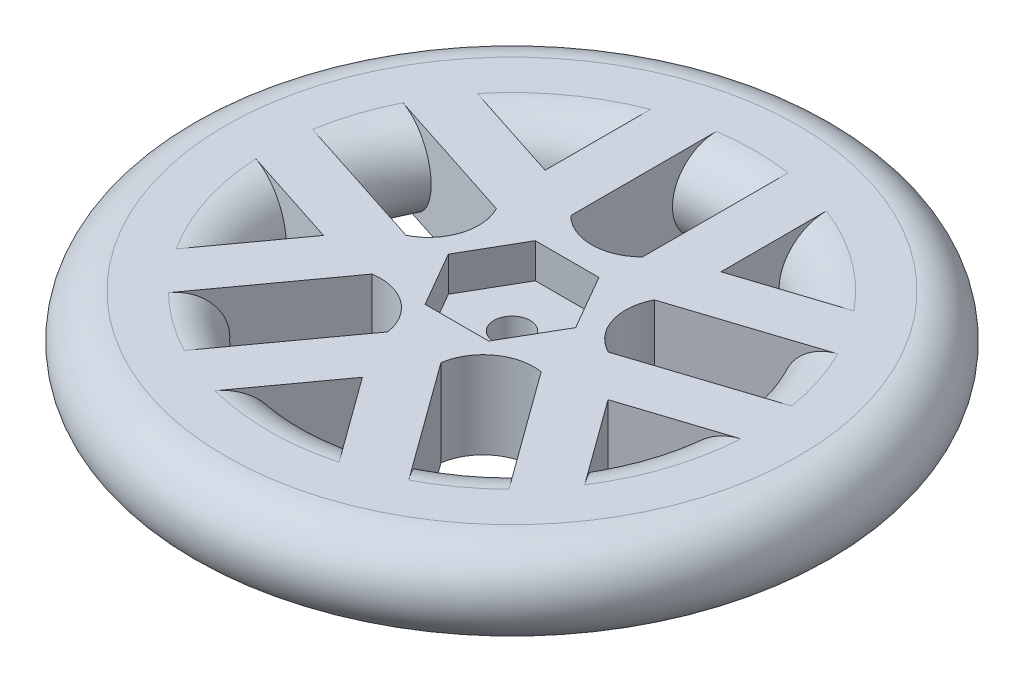
SolidWorks part; units mm, degrees
ref_plane "前视基准面" through (0, 0, 0) normal (0, 0, 1) x (1, 0, 0)
ref_plane "上视基准面" through (0, 0, 0) normal (0, 1, 0) x (1, 0, 0)
ref_plane "右视基准面" through (0, 0, 0) normal (1, 0, 0) x (0, 0, -1)
other "Configuration Table"
sketch "草图1" plane through (0, 0, 0) normal (1, 0, 0) x (0, 0, -1)
  line L0 (0, 0) -> (0, 6.1282) construction
  line L1 (0, 0) -> (9, 0)
  line L2 (0, 0) -> (0, -10)
  line L3 (0, -10) -> (9, -10)
  line L4 (9, 0) -> (9, -10)
  dimension "D1" = 9
  dimension "D2" = 10
revolve "旋转1" add sketch "草图1" angle 360 about L0
sketch "草图2" plane through (0, 0, 0) normal (0, 1, 0) x (1, 0, 0)
  line L1 (7.2733, -0.1394) -> (3.7574, 6.2291)
  line L2 (3.7574, 6.2291) -> (-3.5159, 6.3685)
  line L3 (-3.5159, 6.3685) -> (-7.2733, 0.1394)
  line L4 (-7.2733, 0.1394) -> (-3.7574, -6.2291)
  line L5 (-3.7574, -6.2291) -> (3.5159, -6.3685)
  line L6 (3.5159, -6.3685) -> (7.2733, -0.1394)
  circle A0 centre (0, 0) radius 6.3 construction
  dimension "D1" = 12.6
extrude "切除-拉伸1" cut sketch "草图2" against normal blind 4
sketch "草图4" plane through (0, 0, 0) normal (0, 0, 1) x (1, 0, 0)
  line L0 (0, 0) -> (0, 13.7912) construction
  line L1 (28, 0) -> (33, 0)
  line L4 (33, -10) -> (28, -10)
  arc A0 (28, 0) -> (28, -10) centre (28, -5) ccw
  arc A2 (33, -10) -> (33, 0) centre (33, -5) ccw
  point P4 (0, 0)
  point P6 (0, 0)
  dimension "D1" = 10
  dimension "D4" = 10
  dimension "D2" = 28
  dimension "D3" = 5
  dimension "D5" = 5
revolve "旋转2" add sketch "草图4" angle 360 about L0
sketch "草图5" plane through (0, 0, 0) normal (0, 1, 0) x (1, 0, 0)
  line L0 (0, 30) -> (0, 0) construction
  line L1 (0, 30) -> (-28.5317, 9.2705) construction
  line L2 (-28.5317, 9.2705) -> (-17.6336, -24.2705) construction
  line L3 (-17.6336, -24.2705) -> (17.6336, -24.2705) construction
  line L4 (17.6336, -24.2705) -> (28.5317, 9.2705) construction
  line L5 (28.5317, 9.2705) -> (0, 30) construction
  line L6 (0, 0) -> (-28.5317, 9.2705) construction
  line L7 (-17.6336, -24.2705) -> (0, 0) construction
  line L8 (0, 0) -> (17.6336, -24.2705) construction
  line L9 (28.5317, 9.2705) -> (0, 0) construction
  line L10 (0, 0) -> (-14.2658, 19.6353) construction
  line L11 (0, 0) -> (14.2658, 19.6353) construction
  line L12 (0, 0) -> (23.0826, -7.5) construction
  line L13 (0, 0) -> (23.0826, -7.5) construction
  line L14 (0, 0) -> (0, -24.2705) construction
  line L15 (0, 0) -> (-23.0826, -7.5) construction
  line L16 (-7.1329, 9.8176) -> (-7.1329, 27.0762) construction
  line L17 (7.1329, 9.8176) -> (7.1329, 27.0762) construction
  line L18 (4.1329, 10.9069) -> (4.1329, 27.0762)
  line L19 (-4.1329, 10.9069) -> (-4.1329, 27.0762)
  line L20 (10.1329, 8.9205) -> (10.1329, 27.0762)
  line L21 (-10.1329, 8.9205) -> (-10.1329, 27.0762)
  line L22 (4.1329, 27.0762) -> (4.1329, 29.0762)
  line L23 (4.1329, 29.0762) -> (10.1329, 29.0762)
  line L24 (10.1329, 29.0762) -> (10.1329, 27.0762)
  line L25 (-10.1329, 27.0762) -> (-10.1329, 29.0762)
  line L26 (-10.1329, 29.0762) -> (-4.1329, 29.0762)
  line L27 (-4.1329, 29.0762) -> (-4.1329, 27.0762)
  line L28 (11.6152, -6.8804) -> (28.8823, -1.27)
  line L29 (11.6502, -0.5602) -> (27.0282, 4.4364)
  line L30 (27.0282, 4.4364) -> (28.9303, 5.0544)
  line L31 (28.9303, 5.0544) -> (30.7844, -0.6519)
  line L32 (30.7844, -0.6519) -> (28.8823, -1.27)
  line L33 (26.376, 12.9157) -> (24.4739, 12.2977)
  line L34 (24.5219, 18.622) -> (26.376, 12.9157)
  line L35 (22.6198, 18.004) -> (24.5219, 18.622)
  line L36 (9.0959, 7.301) -> (24.4739, 12.2977)
  line L37 (5.3527, 12.3936) -> (22.6198, 18.004)
  line L38 (-2.9544, -13.1728) -> (7.7173, -27.8611)
  line L39 (3.0673, -11.2531) -> (12.5714, -24.3344)
  line L40 (12.5714, -24.3344) -> (13.747, -25.9524)
  line L41 (13.747, -25.9524) -> (8.8929, -29.4791)
  line L42 (8.8929, -29.4791) -> (7.7173, -27.8611)
  line L43 (20.4342, -21.0939) -> (19.2586, -19.4758)
  line L44 (25.2883, -17.5672) -> (20.4342, -21.0939)
  line L45 (24.1127, -15.9491) -> (25.2883, -17.5672)
  line L46 (9.7545, -6.3946) -> (19.2586, -19.4758)
  line L47 (13.4411, -1.2609) -> (24.1127, -15.9491)
  line L48 (-13.4411, -1.2609) -> (-24.1127, -15.9491)
  line L49 (-9.7545, -6.3946) -> (-19.2586, -19.4758)
  line L50 (-19.2586, -19.4758) -> (-20.4342, -21.0939)
  line L51 (-20.4342, -21.0939) -> (-25.2883, -17.5672)
  line L52 (-25.2883, -17.5672) -> (-24.1127, -15.9491)
  line L53 (-13.747, -25.9524) -> (-12.5714, -24.3344)
  line L54 (-8.8929, -29.4791) -> (-13.747, -25.9524)
  line L55 (-7.7173, -27.8611) -> (-8.8929, -29.4791)
  line L56 (-3.0673, -11.2531) -> (-12.5714, -24.3344)
  line L57 (2.9544, -13.1728) -> (-7.7173, -27.8611)
  line L58 (-5.3527, 12.3936) -> (-22.6198, 18.004)
  line L59 (-9.0959, 7.301) -> (-24.4739, 12.2977)
  line L60 (-24.4739, 12.2977) -> (-26.376, 12.9157)
  line L61 (-26.376, 12.9157) -> (-24.5219, 18.622)
  line L62 (-24.5219, 18.622) -> (-22.6198, 18.004)
  line L63 (-28.9303, 5.0544) -> (-27.0282, 4.4364)
  line L64 (-30.7844, -0.6519) -> (-28.9303, 5.0544)
  line L65 (-28.8823, -1.27) -> (-30.7844, -0.6519)
  line L66 (-11.6502, -0.5602) -> (-27.0282, 4.4364)
  line L67 (-11.6152, -6.8804) -> (-28.8823, -1.27)
  circle A0 centre (0, 0) radius 24.2705 construction
  arc A1 (-7.1329, 9.8176) -> (7.1329, 9.8176) centre (0, 15) ccw construction
  circle A2 centre (0, 0) radius 28 construction
  arc A3 (-4.1329, 10.9069) -> (4.1329, 10.9069) centre (0, 15) ccw
  arc A4 (-10.1329, 8.9205) -> (10.1329, 8.9205) centre (0, 15) ccw
  arc A5 (9.0959, 7.301) -> (11.6502, -0.5602) centre (14.2658, 4.6353) ccw
  arc A6 (5.3527, 12.3936) -> (11.6152, -6.8804) centre (14.2658, 4.6353) ccw
  arc A7 (9.7545, -6.3946) -> (3.0673, -11.2531) centre (8.8168, -12.1353) ccw
  arc A8 (13.4411, -1.2609) -> (-2.9544, -13.1728) centre (8.8168, -12.1353) ccw
  arc A9 (-3.0673, -11.2531) -> (-9.7545, -6.3946) centre (-8.8168, -12.1353) ccw
  arc A10 (2.9544, -13.1728) -> (-13.4411, -1.2609) centre (-8.8168, -12.1353) ccw
  arc A11 (-11.6502, -0.5602) -> (-9.0959, 7.301) centre (-14.2658, 4.6353) ccw
  arc A12 (-11.6152, -6.8804) -> (-5.3527, 12.3936) centre (-14.2658, 4.6353) ccw
  point P16 (0, 0)
  point P94 (0, 0)
  circle M15 centre (0, 0) radius 28
  dimension "D2" = 17.6336
  dimension "D5" = 2
  dimension "D6" = 2
  dimension "D7" = 5
  dimension "D3" = 3
  dimension "D4" = 3
  dimension "D1" = 5
extrude "凸台-拉伸1" add sketch "草图5" against normal blind 10 contours A12 A4 A6 L37 L20 L22 L18 A3 L19 L27 L21 L58 M15 | L37 A6 A4 L20 | A8 L47 L28 L30 L29 A5 L36 L33 L37 L20 A4 A6 M15 | L47 A8 A6 L28 | L32 L31 L30 L28 M15 | L37 L33 L34 L35 M15 | L24 L23 L22 L20 M15 | L27 L26 L25 L21 M15 | A4 A12 L58 L21 | A10 A12 A4 L21 L58 L60 L59 A11 L66 L63 L67 L48 M15 | L62 L61 L60 L58 M15 | L67 L63 L64 L65 M15 | L67 A12 A10 L48 | A12 L67 L48 L50 L49 A9 L56 L53 L57 L38 A8 A10 M15 | L52 L51 L50 L48 M15 | L57 L53 L54 L55 M15 | L57 A10 A8 L38 | A10 L57 L38 L40 L39 A7 L46 L43 L47 L28 A6 A8 M15 | L42 L41 L40 L38 M15 | L47 L43 L44 L45 M15 | A12 A10 A8 A6 A4
sketch "草图6" plane through (0, -10, 0) normal (0, -1, 0) x (1, 0, 0)
  line L2 (-22.6517, 17.0006) -> (-12.291, 2.7403)
  line L3 (1.192, 12.5362) -> (-9.1687, 26.7965)
  line L4 (-22.0484, 18.2117) -> (-11.5413, 3.75)
  line L5 (0, 12.1353) -> (-10.5071, 26.597)
  line L6 (-21.8811, 17.9815) -> (-11.5413, 3.75) construction
  line L7 (0, 12.1353) -> (-10.5071, 26.597) construction
  line L8 (-21.0776, 18.9171) -> (-10.809, 4.7836)
  line L9 (-1.2093, 11.7582) -> (-11.4779, 25.8916)
  line L10 (12.291, 2.7403) -> (22.6517, 17.0006)
  line L11 (-22.0484, 18.2117) -> (-11.5413, 3.75) construction
  line L12 (-23.0192, 17.5064) -> (-12.291, 2.7403) construction
  line L13 (1.192, 12.5362) -> (-9.5362, 27.3023) construction
  line L14 (10.809, 4.7836) -> (21.0776, 18.9171)
  line L15 (11.4779, 25.8916) -> (1.2093, 11.7582)
  line L16 (9.1687, 26.7965) -> (-1.192, 12.5362)
  line L17 (6.4043, -10.8426) -> (23.1683, -16.2896)
  line L18 (7.8897, -8.8018) -> (24.5045, -14.2002)
  line L19 (28.1713, -2.9152) -> (11.5564, 2.4833)
  line L20 (28.3183, -0.4394) -> (11.5543, 5.0075)
  line L21 (-8.3329, -9.4414) -> (-8.3329, -27.0681)
  line L22 (-5.9329, -10.2234) -> (-5.9329, -27.6933)
  line L23 (5.9329, -27.6933) -> (5.9329, -10.2234)
  line L24 (8.3329, -27.0681) -> (8.3329, -9.4414)
  line L25 (-11.5543, 5.0075) -> (-28.3183, -0.4394)
  line L26 (-11.5564, 2.4833) -> (-28.1713, -2.9152)
  line L27 (-24.5045, -14.2002) -> (-7.8897, -8.8018)
  line L28 (-23.1683, -16.2896) -> (-6.4043, -10.8426)
  arc A1 (-12.291, 2.7403) -> (1.192, 12.5362) centre (-8.8168, 12.1353) ccw
  arc A2 (-11.5413, 3.75) -> (0, 12.1353) centre (-8.8168, 12.1353) ccw
  arc A3 (-11.5413, 3.75) -> (0, 12.1353) centre (-8.8168, 12.1353) ccw construction
  arc A4 (-10.809, 4.7836) -> (-1.2093, 11.7582) centre (-8.8168, 12.1353) ccw
  arc A5 (-9.1687, 26.7965) -> (-11.4779, 25.8916) centre (0, 0) ccw
  arc A6 (-21.0776, 18.9171) -> (-22.6517, 17.0006) centre (0, 0) ccw
  arc A7 (-1.192, 12.5362) -> (12.291, 2.7403) centre (8.8168, 12.1353) ccw
  arc A8 (22.6517, 17.0006) -> (21.0776, 18.9171) centre (0, 0) ccw
  arc A9 (1.2093, 11.7582) -> (10.809, 4.7836) centre (8.8168, 12.1353) ccw
  arc A10 (11.4779, 25.8916) -> (9.1687, 26.7965) centre (0, 0) ccw
  arc A11 (11.5543, 5.0075) -> (6.4043, -10.8426) centre (14.2658, -4.6353) ccw
  arc A12 (23.1683, -16.2896) -> (24.5045, -14.2002) centre (0, 0) ccw
  arc A13 (11.5564, 2.4833) -> (7.8897, -8.8018) centre (14.2658, -4.6353) ccw
  arc A14 (28.1713, -2.9152) -> (28.3183, -0.4394) centre (0, 0) ccw
  arc A15 (8.3329, -9.4414) -> (-8.3329, -9.4414) centre (0, -15) ccw
  arc A16 (-8.3329, -27.0681) -> (-5.9329, -27.6933) centre (0, 0) ccw
  arc A17 (5.9329, -10.2234) -> (-5.9329, -10.2234) centre (0, -15) ccw
  arc A18 (5.9329, -27.6933) -> (8.3329, -27.0681) centre (0, 0) ccw
  arc A19 (-6.4043, -10.8426) -> (-11.5543, 5.0075) centre (-14.2658, -4.6353) ccw
  arc A20 (-28.3183, -0.4394) -> (-28.1713, -2.9152) centre (0, 0) ccw
  arc A21 (-7.8897, -8.8018) -> (-11.5564, 2.4833) centre (-14.2658, -4.6353) ccw
  arc A22 (-24.5045, -14.2002) -> (-23.1683, -16.2896) centre (0, 0) ccw
  point P63 (0, 0)
  dimension "D1" = 3
  dimension "D2" = 1.2
  dimension "D3" = 1.2
  dimension "D4" = 5
extrude "切除-拉伸2" cut sketch "草图6" against normal blind 2.5 contours A19 A1 A7 L16 L3 A5 L9 A4 L8 A6 L2 L25 | A11 L20 L10 A8 L14 A9 L15 A10 L16 L3 A1 A7 | A15 L24 L17 A12 L18 A13 L19 A14 L20 L10 A7 A11 | A19 L28 L21 A16 L22 A17 L23 A18 L24 L17 A11 A15 | L27 A22 L28 L21 A15 A19 A1 L2 L25 A20 L26 A21 | L28 A19 A15 L21 | L24 A15 A11 L17 | L20 A11 A7 L10 | L16 A7 A1 L3 | A1 A19 L25 L2 | A19 A15 A11 A7 A1
sketch "草图7" plane through (0, 0, 0) normal (0, 1, 0) x (1, 0, 0)
  line L1 (7.3323, 0) -> (3.6662, 6.35)
  line L2 (3.6662, 6.35) -> (-3.6662, 6.35)
  line L3 (-3.6662, 6.35) -> (-7.3323, 0)
  line L4 (-7.3323, 0) -> (-3.6662, -6.35)
  line L5 (-3.6662, -6.35) -> (3.6662, -6.35)
  line L6 (3.6662, -6.35) -> (7.3323, 0)
  circle A0 centre (0, 0) radius 6.35 construction
  dimension "D1" = 12.7
extrude "切除-拉伸3" cut sketch "草图7" against normal blind 4
sketch "草图8" plane through (0, -4, 0) normal (0, 1, 0) x (1, 0, 0)
  circle A0 centre (0, 0) radius 2.1
  dimension "D1" = 4.2
extrude "切除-拉伸4" cut sketch "草图8" against normal through all
